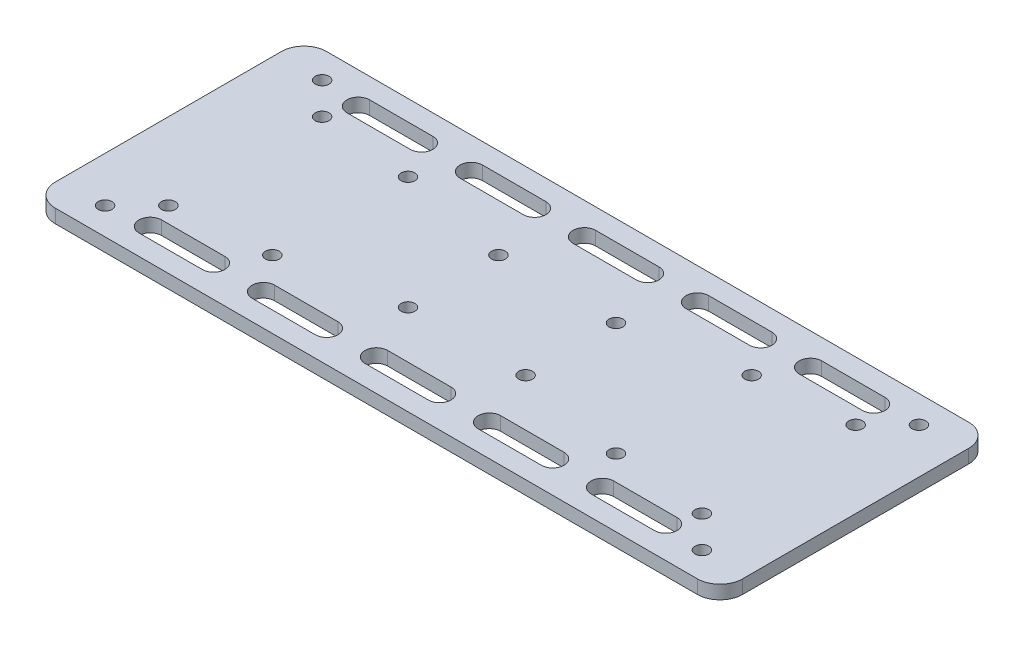
SolidWorks part; units mm, degrees
ref_plane "前视基准面" through (0, 0, 0) normal (0, 0, 1) x (1, 0, 0)
ref_plane "上视基准面" through (0, 0, 0) normal (0, 1, 0) x (1, 0, 0)
ref_plane "右视基准面" through (0, 0, 0) normal (1, 0, 0) x (0, 0, -1)
sketch "草图1" plane through (0, 0, 0) normal (0, 1, 0) x (1, 0, 0)
  line L1 (-76, 30) -> (76, 30)
  line L2 (-76, 30) -> (-76, -30)
  line L3 (-76, -30) -> (76, -30)
  line L4 (76, 30) -> (76, -30)
  line L5 (-76, 30) -> (76, -30) construction
  line L6 (-76, -30) -> (76, 30) construction
  point P0 (0, 0)
  dimension "D1" = 60
  dimension "D2" = 152
extrude "凸台-拉伸1" add sketch "草图1" along normal blind 3
sketch "草图2" plane through (0, 3, 0) normal (0, 1, 0) x (1, 0, 0)
  line L0 (0, 0) -> (0, -56.5945) construction
  line L1 (0, 0) -> (90.2795, 0) construction
  line L3 (-76, -30) -> (76, -30) construction
  circle A0 centre (-66, -24) radius 1.525
  circle A1 centre (-66, 24) radius 1.525
  circle A2 centre (66, -24) radius 1.525
  circle A3 centre (66, 24) radius 1.525
  dimension "D3" = 3.05
  dimension "D1" = 66
  dimension "D2" = 6
extrude "切除-拉伸1" cut sketch "草图2" against normal up to next
fillet "圆角1" radius 5 4 edges at (-76, 1.5, -30) (76, 1.5, -30) (76, 1.5, 30) (-76, 1.5, 30)
sketch "草图3" plane through (0, 3, 0) normal (0, 1, 0) x (1, 0, 0)
  line L0 (0, 0) -> (0, -55.8179) construction
  line L1 (0, 0) -> (89.697, 0) construction
  circle A0 centre (-13, 10) radius 1.525
  circle A1 centre (-38, 15) radius 1.525
  circle A2 centre (-59, 17) radius 1.525
  circle A3 centre (-13, -10) radius 1.525
  circle A4 centre (-38, -15) radius 1.525
  circle A5 centre (-59, -17) radius 1.525
  circle A6 centre (13, -10) radius 1.525
  circle A7 centre (38, -15) radius 1.525
  circle A8 centre (59, -17) radius 1.525
  circle A9 centre (13, 10) radius 1.525
  circle A10 centre (38, 15) radius 1.525
  circle A11 centre (59, 17) radius 1.525
  dimension "D1" = 3.05
  dimension "D2" = 3.05
  dimension "D3" = 3.05
  dimension "D4" = 10
  dimension "D5" = 13
  dimension "D6" = 15
  dimension "D7" = 38
  dimension "D8" = 17
  dimension "D9" = 59
extrude "切除-拉伸2" cut sketch "草图3" against normal up to next
sketch "草图4" plane through (0, 3, 0) normal (0, 1, 0) x (1, 0, 0)
  line L0 (0, 0) -> (0, -41.839) construction
  line L1 (0, 0) -> (87.551, 0) construction
  line L2 (-71, -30) -> (71, -30) construction
  line L3 (-7, -20.5) -> (7, -20.5)
  line L4 (-7, -20.5) -> (-7, -25.5)
  line L5 (-7, -25.5) -> (7, -25.5)
  line L6 (7, -20.5) -> (7, -25.5)
  line L7 (-7, -20.5) -> (7, -25.5) construction
  line L8 (-7, -25.5) -> (7, -20.5) construction
  line L9 (57, -25.5) -> (43, -20.5) construction
  line L10 (-32, -20.5) -> (-18, -20.5)
  line L11 (-32, -20.5) -> (-32, -25.5)
  line L12 (-32, -25.5) -> (-18, -25.5)
  line L13 (-18, -20.5) -> (-18, -25.5)
  line L14 (-32, -20.5) -> (-18, -25.5) construction
  line L15 (-32, -25.5) -> (-18, -20.5) construction
  line L16 (-57, -20.5) -> (-43, -20.5)
  line L17 (-57, -20.5) -> (-57, -25.5)
  line L18 (-57, -25.5) -> (-43, -25.5)
  line L19 (-43, -20.5) -> (-43, -25.5)
  line L20 (-57, -20.5) -> (-43, -25.5) construction
  line L21 (-57, -25.5) -> (-43, -20.5) construction
  line L22 (57, -20.5) -> (43, -25.5) construction
  line L23 (32, -25.5) -> (18, -20.5) construction
  line L24 (32, -20.5) -> (18, -25.5) construction
  line L25 (43, -20.5) -> (43, -25.5)
  line L26 (57, -25.5) -> (43, -25.5)
  line L27 (57, -20.5) -> (57, -25.5)
  line L28 (57, -20.5) -> (43, -20.5)
  line L29 (18, -20.5) -> (18, -25.5)
  line L30 (32, -25.5) -> (18, -25.5)
  line L31 (32, -20.5) -> (32, -25.5)
  line L32 (32, -20.5) -> (18, -20.5)
  line L33 (57, 20.5) -> (43, 25.5) construction
  line L34 (57, 25.5) -> (43, 20.5) construction
  line L35 (57, 20.5) -> (43, 20.5)
  line L36 (57, 20.5) -> (57, 25.5)
  line L37 (57, 25.5) -> (43, 25.5)
  line L38 (43, 20.5) -> (43, 25.5)
  line L39 (32, 20.5) -> (18, 25.5) construction
  line L40 (32, 25.5) -> (18, 20.5) construction
  line L41 (32, 20.5) -> (18, 20.5)
  line L42 (32, 20.5) -> (32, 25.5)
  line L43 (32, 25.5) -> (18, 25.5)
  line L44 (18, 20.5) -> (18, 25.5)
  line L45 (-7, 25.5) -> (7, 20.5) construction
  line L46 (-7, 20.5) -> (7, 25.5) construction
  line L47 (7, 20.5) -> (7, 25.5)
  line L48 (-7, 25.5) -> (7, 25.5)
  line L49 (-7, 20.5) -> (-7, 25.5)
  line L50 (-7, 20.5) -> (7, 20.5)
  line L51 (-32, 25.5) -> (-18, 20.5) construction
  line L52 (-32, 20.5) -> (-18, 25.5) construction
  line L53 (-18, 20.5) -> (-18, 25.5)
  line L54 (-32, 25.5) -> (-18, 25.5)
  line L55 (-32, 20.5) -> (-32, 25.5)
  line L56 (-32, 20.5) -> (-18, 20.5)
  line L57 (-57, 25.5) -> (-43, 20.5) construction
  line L58 (-57, 20.5) -> (-43, 25.5) construction
  line L59 (-43, 20.5) -> (-43, 25.5)
  line L60 (-57, 25.5) -> (-43, 25.5)
  line L61 (-57, 20.5) -> (-57, 25.5)
  line L62 (-57, 20.5) -> (-43, 20.5)
  arc A0 (-7, -25.5) -> (-7, -20.5) centre (-7, -23) cw
  arc A1 (7, -20.5) -> (7, -25.5) centre (7, -23) cw
  arc A2 (-18, -20.5) -> (-18, -25.5) centre (-18, -23) cw
  arc A3 (-32, -25.5) -> (-32, -20.5) centre (-32, -23) cw
  arc A4 (-43, -20.5) -> (-43, -25.5) centre (-43, -23) cw
  arc A5 (-57, -25.5) -> (-57, -20.5) centre (-57, -23) cw
  arc A6 (57, -25.5) -> (57, -20.5) centre (57, -23) ccw
  arc A7 (43, -20.5) -> (43, -25.5) centre (43, -23) ccw
  arc A8 (32, -25.5) -> (32, -20.5) centre (32, -23) ccw
  arc A9 (18, -20.5) -> (18, -25.5) centre (18, -23) ccw
  arc A10 (43, 20.5) -> (43, 25.5) centre (43, 23) cw
  arc A11 (57, 25.5) -> (57, 20.5) centre (57, 23) cw
  arc A12 (18, 20.5) -> (18, 25.5) centre (18, 23) cw
  arc A13 (32, 25.5) -> (32, 20.5) centre (32, 23) cw
  arc A14 (7, 20.5) -> (7, 25.5) centre (7, 23) ccw
  arc A15 (-7, 25.5) -> (-7, 20.5) centre (-7, 23) ccw
  arc A16 (-32, 25.5) -> (-32, 20.5) centre (-32, 23) ccw
  arc A17 (-18, 20.5) -> (-18, 25.5) centre (-18, 23) ccw
  arc A18 (-57, 25.5) -> (-57, 20.5) centre (-57, 23) ccw
  arc A19 (-43, 20.5) -> (-43, 25.5) centre (-43, 23) ccw
  point P4 (0, -23)
  point P16 (-25, -23)
  point P23 (-50, -23)
  point P42 (50, -23)
  point P43 (25, -23)
  point P50 (50, 23)
  point P57 (25, 23)
  point P64 (0, 23)
  point P71 (-25, 23)
  point P78 (-50, 23)
  dimension "D2" = 2.5
  dimension "D5" = 2.5
  dimension "D8" = 2.5
  dimension "D1" = 14
  dimension "D3" = 7
  dimension "D4" = 14
  dimension "D6" = 25
  dimension "D7" = 14
  dimension "D9" = 25
extrude "切除-拉伸3" cut sketch "草图4" against normal up to next (3 mm away) contours A5 L17 | L19 L16 L17 L18 | A4 L19 | A3 L11 | L13 L10 L11 L12 | A2 L13 | A0 L4 | L6 L3 L4 L5 | A1 L6 | L29 A9 | L31 L32 L29 L30 | L31 A8 | L25 A7 | L27 L28 L25 L26 | L27 A6 | L61 A18 | L61 L62 L59 L60 | L59 A19 | L55 A16 | L55 L56 L53 L54 | L53 A17 | L49 A15 | L49 L50 L47 L48 | L47 A14 | A12 L44 | L44 L41 L42 L43 | A13 L42 | A10 L38 | L38 L35 L36 L37 | A11 L36
